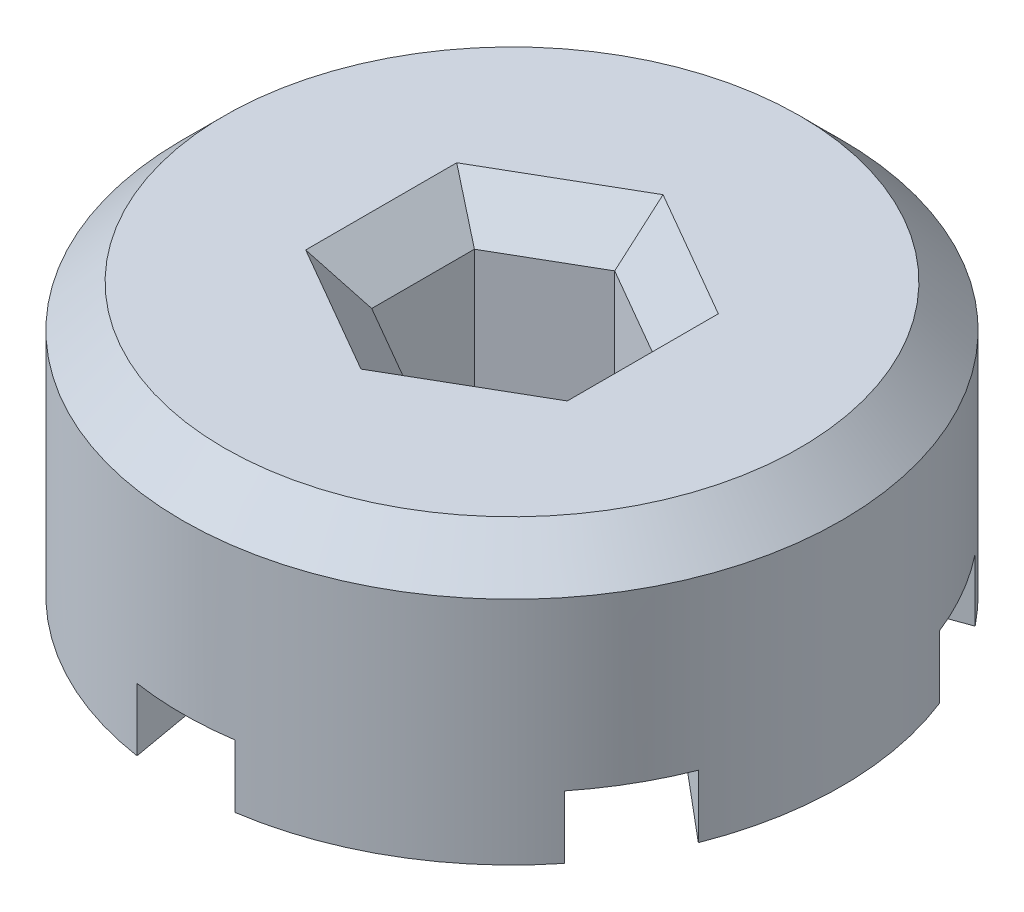
SolidWorks part; units mm, degrees
ref_plane "Front Plane" through (0, 0, 0) normal (0, 0, 1) x (1, 0, 0)
ref_plane "Top Plane" through (0, 0, 0) normal (0, 1, 0) x (1, 0, 0)
ref_plane "Right Plane" through (0, 0, 0) normal (1, 0, 0) x (0, 0, -1)
sketch "Sketch1" plane through (0, 0, 0) normal (0, 1, 0) x (1, 0, 0)
  circle A0 centre (0, 0) radius 15.75
  dimension "D1" = 31.5
extrude "Boss-Extrude1" add sketch "Sketch1" along normal blind 10
sketch "Sketch2" plane through (0, 10, 0) normal (0, 1, 0) x (1, 0, 0)
  line L0 (0, -5.5) -> (0, 5.5) construction
  line L1 (4.25, 2.4537) -> (0, 4.9075)
  line L2 (0, 4.9075) -> (-4.25, 2.4537)
  line L3 (-4.25, 2.4537) -> (-4.25, -2.4537)
  line L4 (-4.25, -2.4537) -> (0, -4.9075)
  line L5 (0, -4.9075) -> (4.25, -2.4537)
  line L6 (4.25, -2.4537) -> (4.25, 2.4537)
  circle A0 centre (0, 0) radius 4.25 construction
  dimension "D1" = 8.5
extrude "Cut-Extrude1" cut sketch "Sketch2" against normal blind 10
sketch "Sketch3" plane through (0, 0, 0) normal (0, -1, 0) x (1, 0, 0)
  line L0 (0, 0) -> (-43301.2702, -25000) construction
  line L1 (0, 0) -> (0, 50000) construction
  line L2 (0, 0) -> (43301.2702, -25000) construction
  line L3 (0, 0) -> (-50000, 0) construction
  line L4 (0, 0) -> (-7.8, 0) construction
  line L5 (-7.8, 0) -> (-38310.0222, -32139.3805) construction
  line L6 (-7.8, 0) -> (-38310.0222, 32139.3805) construction
  line L7 (-7.8, 0) -> (-14.6603, -5.7565)
  line L8 (-7.8, 0) -> (-14.6603, 5.7565)
  line L9 (-3.9, 6.755) -> (-12.3154, 9.818)
  line L10 (-3.9, 6.755) -> (-2.3449, 15.5745)
  line L11 (3.9, 6.755) -> (2.3449, 15.5745)
  line L12 (3.9, 6.755) -> (12.3154, 9.818)
  line L13 (7.8, 0) -> (14.6603, 5.7565)
  line L14 (7.8, 0) -> (14.6603, -5.7565)
  line L15 (3.9, -6.755) -> (12.3154, -9.818)
  line L16 (3.9, -6.755) -> (2.3449, -15.5745)
  line L17 (-3.9, -6.755) -> (-2.3449, -15.5745)
  line L18 (-3.9, -6.755) -> (-12.3154, -9.818)
  line L21 (5.5, 0) -> (-5.5, 0) construction
  circle A0 centre (0, 0) radius 15.75 construction
  arc A1 (-14.6603, 5.7565) -> (-14.6603, -5.7565) centre (0, 0) ccw
  arc A2 (-2.3449, 15.5745) -> (-12.3154, 9.818) centre (0, 0) ccw
  arc A3 (12.3154, 9.818) -> (2.3449, 15.5745) centre (0, 0) ccw
  arc A4 (14.6603, -5.7565) -> (14.6603, 5.7565) centre (0, 0) ccw
  arc A5 (2.3449, -15.5745) -> (12.3154, -9.818) centre (0, 0) ccw
  arc A6 (-12.3154, -9.818) -> (-2.3449, -15.5745) centre (0, 0) ccw
  point P43 (0, 0)
  circle M10 centre (0, 0) radius 15.75
  dimension "D1" = 60
  dimension "D2" = 60
  dimension "D3" = 30
  dimension "D4" = 7.8
  dimension "D5" = 40
  dimension "D6" = 40
  dimension "D7" = 6
extrude "Boss-Extrude2" add sketch "Sketch3" along normal blind 3 contours L7 L8 M10 | L17 L18 M10 | L15 L16 M10 | L13 L14 M10 | L11 L12 M10 | L9 L10 M10
sketch "Sketch4" plane through (0, 10, 0) normal (0, 1, 0) x (1, 0, 0)
  circle A0 centre (0, 0) radius 7.1
  dimension "D1" = 14.2
extrude "Cut-Extrude2" [suppressed] cut sketch "Sketch4" against normal blind 3
chamfer "Chamfer1" distance 2 angle 45 7 edges at (0, 10, 15.75) (2.125, 10, -3.6806) (-2.125, 10, -3.6806) (-4.25, 10, 0) (-2.125, 10, 3.6806) (2.125, 10, 3.6806) (4.25, 10, 0)
